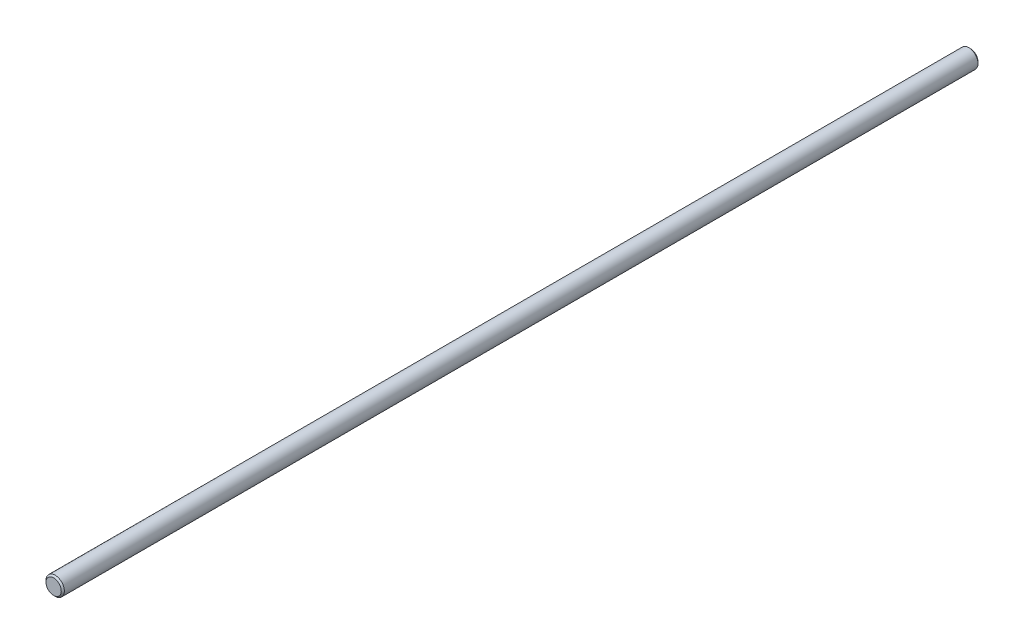
SolidWorks part; units mm, degrees
material "AISI Type A2 Tool Steel"
ref_plane "Front Plane" through (0, 0, 0) normal (0, 0, 1) x (1, 0, 0)
ref_plane "Top Plane" through (0, 0, 0) normal (0, 1, 0) x (1, 0, 0)
ref_plane "Right Plane" through (0, 0, 0) normal (1, 0, 0) x (0, 0, -1)
sketch "Sketch1" plane through (0, 0, 0) normal (0, 0, 1) x (1, 0, 0)
  circle A0 centre (0, 0) radius 3
  dimension "D1" = 6
extrude "Boss-Extrude1" add sketch "Sketch1" along normal blind 300
chamfer "Chamfer1" distance 0.5 angle 45 2 edges at (3, 0, 0) (3, 0, 300)
